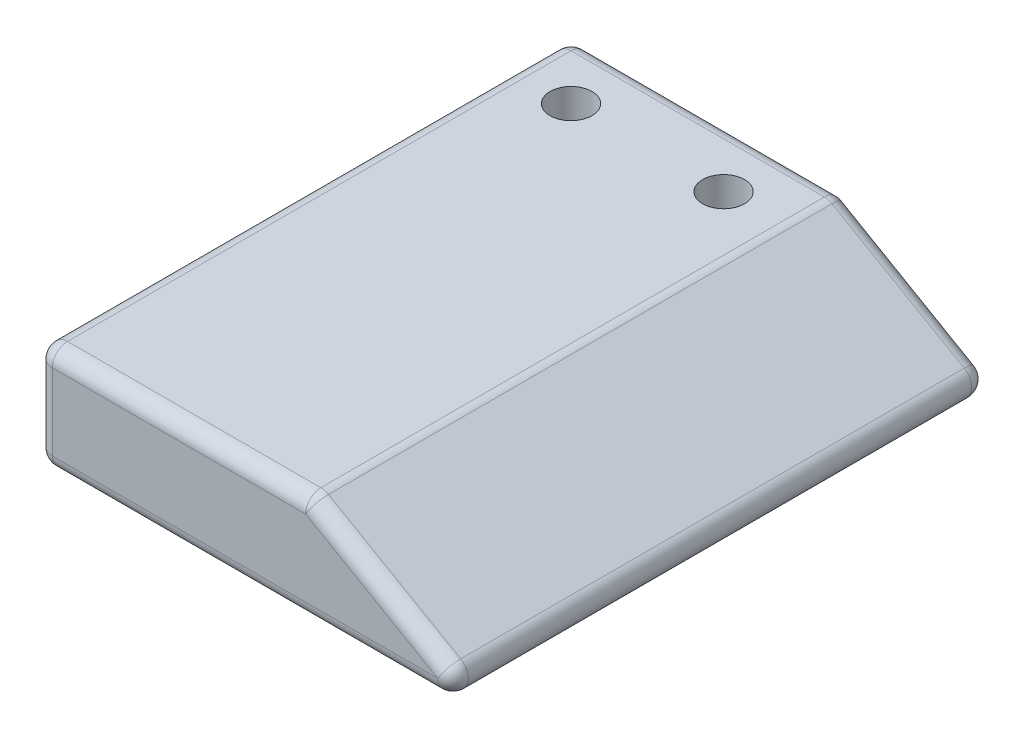
SolidWorks part; units mm, degrees
ref_plane "Front Plane" through (0, 0, 0) normal (0, 0, 1) x (1, 0, 0)
ref_plane "Top Plane" through (0, 0, 0) normal (0, 1, 0) x (1, 0, 0)
ref_plane "Right Plane" through (0, 0, 0) normal (1, 0, 0) x (0, 0, -1)
sketch "Sketch1" plane through (0, 0, 0) normal (0, 0, 1) x (1, 0, 0)
  line L0 (0, 0) -> (0, 14)
  line L1 (0, 14) -> (35.7513, 14)
  line L2 (35.7513, 14) -> (60, 0)
  line L3 (60, 0) -> (0, 0)
  dimension "D1" = 60
  dimension "D2" = 30
  dimension "D3" = 14
extrude "Boss-Extrude1" add sketch "Sketch1" along normal blind 70
hole_wizard "CSK for M5 Hex Socket Countersunk Cap Screw1" positions "Sketch2" profile "Sketch3" countersink size "M5" standard "ISO" end condition through all
sketch "Sketch2" plane through (0, 0, 0) normal (0, -1, 0) x (-1, 0, 0)
  line L0 (0, 0) -> (-60, 0) construction
  line L1 (0, -70) -> (0, 0) construction
  point P0 (-8, -8)
  point P2 (-28, -8)
  point P9 (0, 0)
  dimension "D1" = 8
  dimension "D2" = 8
  dimension "D3" = 20
sketch "Sketch3" plane through (8, 0, 8) normal (1, 0, 0) x (0, 0, -1)
  line L0 (0, 0) -> (0, 14)
  line L1 (0, 14) -> (2.75, 14)
  line L2 (2.75, 14) -> (2.75, 2.85)
  line L3 (2.75, 2.85) -> (5.6, 0)
  line L5 (5.6, 0) -> (0, 0)
  line L6 (-2.75, 2.85) -> (-5.6, 0) construction
  line L11 (0, -6.35) -> (0, 107.95) construction
  dimension "Thru Hole Dia." = 5.5
  dimension "Thru Hole Depth" = 14
  dimension "Near C'Sink Dia." = 11.2
  dimension "Near C'Sink Angle" = 90
fillet "Fillet1" radius 2 12 edges at (60, 0, 35) (35.7513, 14, 35) (47.8756, 7, 0) (17.8756, 14, 0) (30, 0, 0) (17.8756, 14, 70) (47.8756, 7, 70) (30, 0, 70) (0, 14, 35) (0, 7, 70) (0, 0, 35) (0, 7, 0)
